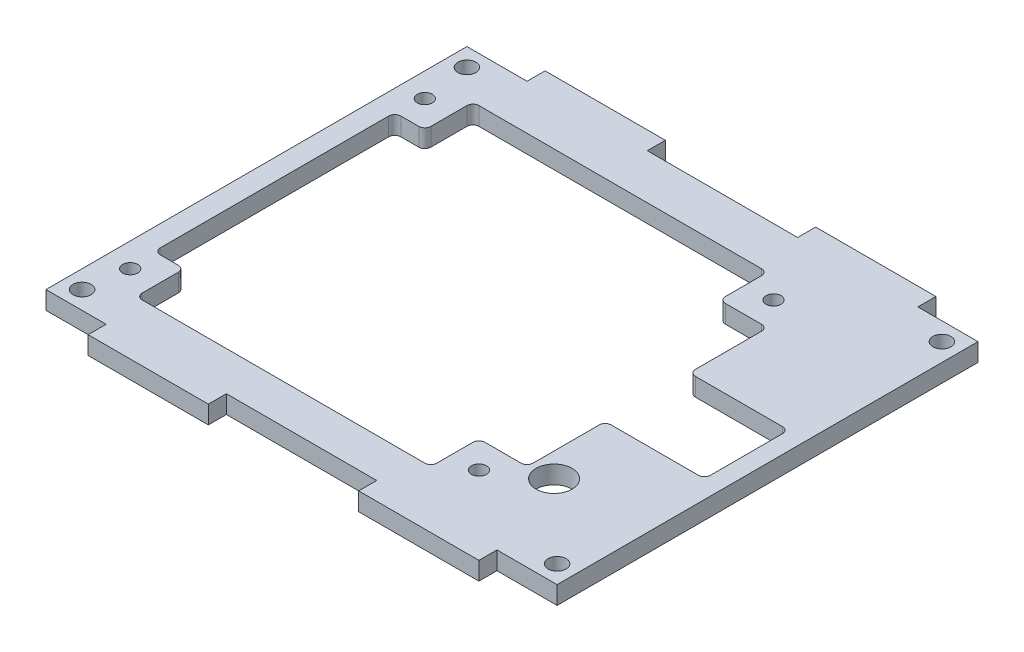
SolidWorks part; units mm, degrees
ref_plane "Front Plane" through (0, 0, 0) normal (0, 0, 1) x (1, 0, 0)
ref_plane "Top Plane" through (0, 0, 0) normal (0, 1, 0) x (1, 0, 0)
ref_plane "Right Plane" through (0, 0, 0) normal (1, 0, 0) x (0, 0, -1)
sketch "Sketch1" plane through (0, 0, 0) normal (0, 1, 0) x (1, 0, 0)
  line L1 (-42.5, 35) -> (42.5, 35)
  line L2 (-42.5, 35) -> (-42.5, -35)
  line L3 (-42.5, -35) -> (42.5, -35)
  line L4 (42.5, 35) -> (42.5, -35)
  line L5 (-42.5, 35) -> (42.5, -35) construction
  line L6 (-42.5, -35) -> (42.5, 35) construction
  point P0 (0, 0)
  dimension "D1" = 85
  dimension "D2" = 70
extrude "Boss-Extrude1" add sketch "Sketch1" along normal blind 3
sketch "Sketch2" plane through (0, 3, 0) normal (0, 1, 0) x (1, 0, 0)
  line L0 (-38.5, 24) -> (-38.5, -25) construction
  line L1 (-38.5, -25) -> (19.5, -25) construction
  line L2 (19.5, -25) -> (19.5, 24) construction
  line L3 (19.5, 24) -> (-38.5, 24) construction
  line L4 (-42.5, 35) -> (-42.5, -35) construction
  line L5 (-42.5, -35) -> (42.5, -35) construction
  circle A0 centre (-38.5, 24) radius 1.25
  circle A1 centre (-38.5, -25) radius 1.25
  circle A2 centre (19.5, -25) radius 1.25
  circle A3 centre (19.5, 24) radius 1.25
  dimension "D1" = 2.5
  dimension "D2" = 4
  dimension "D3" = 49
  dimension "D4" = 58
  dimension "D5" = 10
extrude "Cut-Extrude1" cut sketch "Sketch2" against normal through all
sketch "Sketch3" plane through (0, 3, 0) normal (0, 1, 0) x (1, 0, 0)
  line L0 (-42.5, -35) -> (42.5, -35) construction
  line L1 (-12.5, 38) -> (-32.5, 38)
  line L2 (-12.5, 38) -> (-12.5, 35)
  line L3 (-12.5, 35) -> (-32.5, 35)
  line L4 (-32.5, 38) -> (-32.5, 35)
  line L5 (-12.5, 38) -> (-32.5, 35) construction
  line L6 (-12.5, 35) -> (-32.5, 38) construction
  line L7 (32.5, 38) -> (12.5, 38)
  line L8 (32.5, 38) -> (32.5, 35)
  line L9 (32.5, 35) -> (12.5, 35)
  line L10 (12.5, 38) -> (12.5, 35)
  line L11 (32.5, 38) -> (12.5, 35) construction
  line L12 (32.5, 35) -> (12.5, 38) construction
  line L13 (12.5, -35) -> (32.5, -35)
  line L14 (12.5, -35) -> (12.5, -38)
  line L15 (12.5, -38) -> (32.5, -38)
  line L16 (32.5, -35) -> (32.5, -38)
  line L17 (12.5, -35) -> (32.5, -38) construction
  line L18 (12.5, -38) -> (32.5, -35) construction
  line L19 (-32.5, -35) -> (-12.5, -35)
  line L20 (-32.5, -35) -> (-32.5, -38)
  line L21 (-32.5, -38) -> (-12.5, -38)
  line L22 (-12.5, -35) -> (-12.5, -38)
  line L23 (-32.5, -35) -> (-12.5, -38) construction
  line L24 (-32.5, -38) -> (-12.5, -35) construction
  line L25 (42.5, 35) -> (-42.5, 35) construction
  line L26 (-42.5, 36.5) -> (-22.5, 36.5) construction
  line L27 (-22.5, 36.5) -> (22.5, 36.5) construction
  line L28 (22.5, 36.5) -> (42.5, 36.5) construction
  line L29 (-42.5, -36.5) -> (-22.5, -36.5) construction
  line L30 (-22.5, -36.5) -> (22.5, -36.5) construction
  line L31 (22.5, -36.5) -> (42.5, -36.5) construction
  line L32 (42.5, 36.5) -> (42.5, -36.5) construction
  line L33 (-42.5, -36.5) -> (-42.5, 36.5) construction
  line L34 (-42.5, 35) -> (-42.5, -35) construction
  line L35 (42.5, -35) -> (42.5, 35) construction
  line L49 (0, 35) -> (0, -35) construction
  point P0 (-22.5, 36.5)
  point P5 (22.5, 36.5)
  point P10 (22.5, -36.5)
  point P15 (-22.5, -36.5)
  point P36 (44, 0)
  point P41 (-44, 0)
  point P50 (0, 0)
  dimension "D1" = 3
  dimension "D2" = 20
  dimension "D3" = 20
extrude "Boss-Extrude2" add sketch "Sketch3" against normal up to surface (3 mm away) up to face at (19.5, 0, -22.75)
sketch "Sketch4" plane through (0, 3, 0) normal (0, 1, 0) x (1, 0, 0)
  line L0 (-39.5, -32) -> (39.5, -32) construction
  line L1 (39.5, -32) -> (39.5, 32) construction
  line L2 (39.5, 32) -> (-39.5, 32) construction
  line L3 (-39.5, 32) -> (-39.5, -32) construction
  line L4 (-39.5, -32) -> (39.5, 32) construction
  line L5 (32.5, -35) -> (42.5, -35) construction
  line L6 (42.5, -35) -> (42.5, 35) construction
  circle A0 centre (-39.5, -32) radius 1.5
  circle A1 centre (39.5, -32) radius 1.5
  circle A2 centre (39.5, 32) radius 1.5
  circle A3 centre (-39.5, 32) radius 1.5
  dimension "D1" = 3
  dimension "D2" = 3
  dimension "D3" = 3
extrude "Cut-Extrude2" cut sketch "Sketch4" against normal blind 10
sketch "Sketch5" plane through (0, 3, 0) normal (0, 1, 0) x (1, 0, 0)
  line L0 (-34, 27.5) -> (-34, 19.5)
  line L1 (15, -28.5) -> (-34, -28.5)
  line L2 (23, -20.5) -> (23, 19.5)
  line L3 (15, 27.5) -> (-34, 27.5)
  line L4 (-42, -20.5) -> (-42, 18.5731) construction
  line L5 (-39, -20.5) -> (-39, 19.5)
  line L7 (-34, 19.5) -> (-39, 19.5)
  line L8 (15, 27.5) -> (15, 19.5)
  line L9 (15, 19.5) -> (23, 19.5)
  line L10 (23, -20.5) -> (15, -20.5)
  line L11 (15, -20.5) -> (15, -28.5)
  line L12 (-34, -28.5) -> (-34, -20.5)
  line L13 (-34, -20.5) -> (-39, -20.5)
  circle A0 centre (19.5, -25) radius 1.25 construction
  circle A1 centre (-38.5, -25) radius 1.25 construction
  circle A2 centre (-38.5, 24) radius 1.25 construction
  point P0 (-9.5, -0.5)
  dimension "D1" = 3.5
  dimension "D2" = 3.5
  dimension "D3" = 3.5
  dimension "D4" = 3.5
  dimension "D5" = 8
  dimension "D6" = 8
  dimension "D7" = 3
extrude "Cut-Extrude3" cut sketch "Sketch5" against normal blind 10
fillet "Fillet1" radius 1 12 edges at (-39, 1.5, -19.5) (-34, 1.5, -19.5) (-34, 1.5, -27.5) (15, 1.5, -27.5) (15, 1.5, -19.5) (23, 1.5, -19.5) (23, 1.5, 20.5) (15, 1.5, 20.5) (15, 1.5, 28.5) (-34, 1.5, 28.5) (-34, 1.5, 20.5) (-39, 1.5, 20.5)
sketch "Sketch6" plane through (0, 3, 0) normal (0, 1, 0) x (1, 0, 0)
  line L0 (23, -7.5) -> (39.5, -7.5)
  line L1 (23, -19.5) -> (23, 18.5) construction
  line L2 (23, -7.5) -> (23, 6.5)
  line L3 (23, 6.5) -> (39.5, 6.5)
  line L4 (39.5, -7.5) -> (39.5, 6.5)
  line L5 (23, -19.5) -> (23, 18.5) construction
  circle A3 centre (19.5, 24) radius 1.25 construction
  point P8 (23, -0.5)
  dimension "D2" = 20
  dimension "D1" = 14
extrude "Cut-Extrude4" cut sketch "Sketch6" against normal through all
fillet "Fillet2" radius 1 4 edges at (23, 1.5, 7.5) (23, 1.5, -6.5) (39.5, 1.5, -6.5) (39.5, 1.5, 7.5)
sketch "Sketch7" [suppressed] plane through (0, 3, 0) normal (0, 1, 0) x (1, 0, 0)
  line L1 (32.5, 32.5) -> (-32.5, 32.5)
  line L2 (32.5, 32.5) -> (32.5, -32.5)
  line L3 (32.5, -32.5) -> (-32.5, -32.5)
  line L4 (-32.5, 32.5) -> (-32.5, -32.5)
  line L5 (32.5, 32.5) -> (-32.5, -32.5) construction
  line L6 (32.5, -32.5) -> (-32.5, 32.5) construction
  point P0 (0, 0)
  dimension "D1" = 65
  dimension "D2" = 65
extrude "Cut-Extrude5" [suppressed] cut sketch "Sketch7" against normal blind 6
sketch "Sketch8" [suppressed] plane through (0, 3, 0) normal (0, 1, 0) x (1, 0, 0)
  line L0 (-42.5, 20) -> (-32.5, 20) construction
  line L2 (-32.5, 32.5) -> (-32.5, -32.5) construction
  line L4 (32.5, -20) -> (42.5, -20) construction
  line L6 (42.5, -35) -> (42.5, 35) construction
  line L8 (32.5, -35) -> (42.5, -35) construction
  line L9 (-32.5, 35) -> (-42.5, 35) construction
  line L10 (-42.5, 35) -> (-42.5, -35) construction
  line L11 (32.5, -32.5) -> (32.5, 32.5) construction
  circle A1 centre (37.5, -20) radius 3
  dimension "D1" = 6
  dimension "D2" = 15
  dimension "D3" = 15
extrude "Cut-Extrude6" [suppressed] cut sketch "Sketch8" against normal blind 6
sketch "Sketch9" [suppressed] plane through (0, 0, 0) normal (0, -1, 0) x (1, 0, 0)
  line L0 (42.5, 35) -> (42.5, -35) construction
  line L1 (-36.75, -30.4123) -> (-39.5, -28.8246)
  line L2 (-39.5, -28.8246) -> (-42.25, -30.4123)
  line L3 (-42.25, -30.4123) -> (-42.25, -33.5877) construction
  line L4 (-42.25, -33.5877) -> (-39.5, -35.1754) construction
  line L5 (-39.5, -35.1754) -> (-36.75, -33.5877) construction
  line L6 (-36.75, -33.5877) -> (-36.75, -30.4123)
  line L7 (-42.25, 30.4123) -> (-39.5, 28.8246)
  line L8 (-39.5, 28.8246) -> (-36.75, 30.4123)
  line L9 (-36.75, 30.4123) -> (-36.75, 33.5877)
  line L10 (-36.75, 33.5877) -> (-39.5, 35.1754) construction
  line L11 (-39.5, 35.1754) -> (-42.25, 33.5877) construction
  line L12 (-42.25, 33.5877) -> (-42.25, 30.4123) construction
  line L13 (36.75, 30.4123) -> (39.5, 28.8246)
  line L14 (39.5, 28.8246) -> (42.25, 30.4123)
  line L15 (42.25, 30.4123) -> (42.25, 33.5877) construction
  line L16 (42.25, 33.5877) -> (39.5, 35.1754) construction
  line L17 (39.5, 35.1754) -> (36.75, 33.5877) construction
  line L18 (36.75, 33.5877) -> (36.75, 30.4123)
  line L19 (36.75, -30.4123) -> (36.75, -33.5877)
  line L20 (36.75, -33.5877) -> (39.5, -35.1754) construction
  line L21 (39.5, -35.1754) -> (42.25, -33.5877) construction
  line L22 (42.25, -33.5877) -> (42.25, -30.4123) construction
  line L23 (42.25, -30.4123) -> (39.5, -28.8246)
  line L24 (39.5, -28.8246) -> (36.75, -30.4123)
  line L25 (-42.5, -35) -> (-42.5, 35) construction
  line L26 (-42.25, 30.4123) -> (-43.6641, 31.2287)
  line L27 (-43.6641, 31.2287) -> (-43.6641, 38.3487)
  line L28 (-43.6641, 38.3487) -> (-36.75, 38.3487)
  line L29 (-36.75, 38.3487) -> (-36.75, 33.5877)
  line L30 (-42.25, -30.4123) -> (-44.0078, -31.4272)
  line L31 (-44.0078, -31.4272) -> (-46.1016, -35.5535)
  line L32 (-46.1016, -35.5535) -> (-36.75, -35.5535)
  line L33 (-36.75, -35.5535) -> (-36.75, -33.5877)
  line L35 (36.75, -33.5877) -> (36.75, -36.7514)
  line L36 (36.75, -36.7514) -> (45.6714, -36.7514)
  line L37 (45.6714, -36.7514) -> (45.6714, -32.3877)
  line L38 (45.6714, -32.3877) -> (42.25, -30.4123)
  line L39 (42.25, 30.4123) -> (44.2756, 31.5817)
  line L40 (44.2756, 31.5817) -> (44.2756, 37.6051)
  line L41 (44.2756, 37.6051) -> (36.75, 37.6051)
  line L42 (36.75, 37.6051) -> (36.75, 33.5877)
  circle A0 centre (-39.5, -32) radius 2.75 construction
  circle A1 centre (-39.5, 32) radius 2.75 construction
  circle A2 centre (39.5, 32) radius 2.75 construction
  circle A3 centre (39.5, -32) radius 2.75 construction
  dimension "D1" = 5.5
extrude "Cut-Extrude7" [suppressed] cut sketch "Sketch9" against normal blind 6
sketch "Sketch10" [suppressed] plane through (0, 3, 0) normal (0, 1, 0) x (1, 0, 0)
  line L0 (42.5, 0) -> (37.5, 0) construction
  line L1 (42.5, -30.5566) -> (42.5, 30.5566) construction
  line L2 (37.5, 0) -> (32.5, 0) construction
  line L3 (32.5, -32.5) -> (32.5, 32.5) construction
  line L4 (-37.5, 0) -> (-32.5, 0) construction
  line L5 (-32.5, 32.5) -> (-32.5, -32.5) construction
  line L6 (-37.5, 0) -> (-42.5, 0) construction
  line L7 (-42.5, 30.5566) -> (-42.5, -30.5566) construction
  circle A0 centre (37.5, 0) radius 1.5
  circle A1 centre (-37.5, 0) radius 1.5
  dimension "D1" = 3
extrude "Cut-Extrude8" [suppressed] cut sketch "Sketch10" against normal blind 6
sketch "Sketch11" plane through (0, 3, 0) normal (0, 1, 0) x (1, 0, 0)
  circle A0 centre (27, -20) radius 3
  circle A1 centre (19.5, -25) radius 1.25 construction
  dimension "D1" = 7.5
  dimension "D2" = 5
  dimension "D3" = 6
extrude "Cut-Extrude9" cut sketch "Sketch11" against normal blind 10
